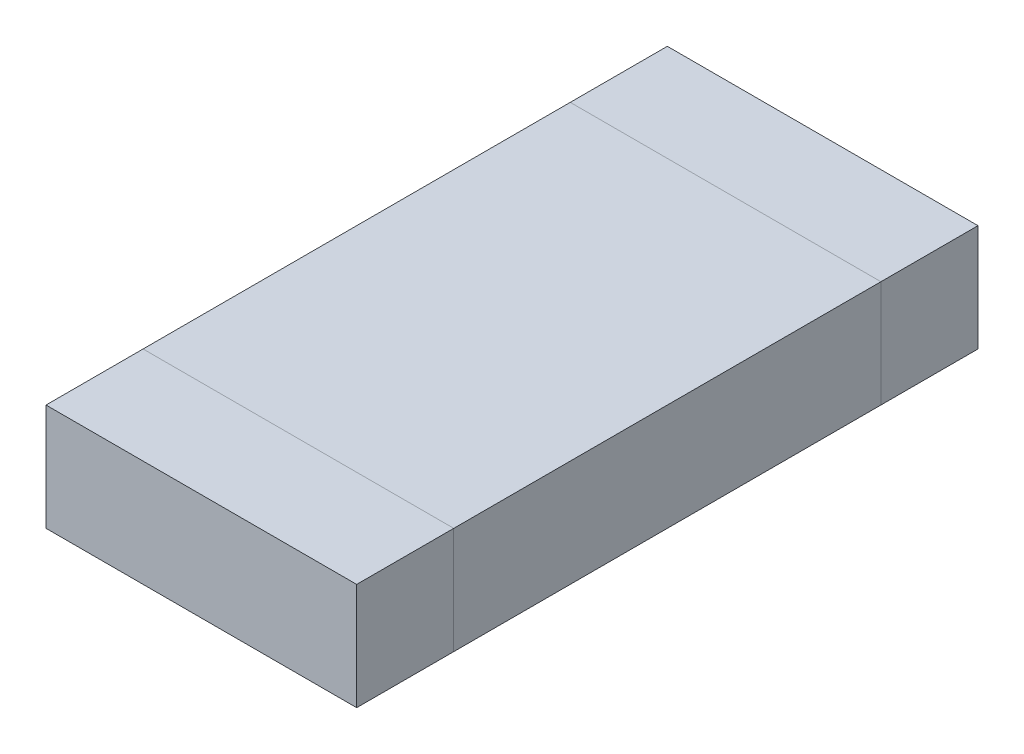
SolidWorks part; units mm, degrees
ref_plane "Front Plane" through (0, 0, 0) normal (0, 0, 1) x (1, 0, 0)
ref_plane "Top Plane" through (0, 0, 0) normal (0, 1, 0) x (1, 0, 0)
ref_plane "Right Plane" through (0, 0, 0) normal (1, 0, 0) x (0, 0, -1)
sketch "MainBodyS" plane through (0, 0, 0) normal (0, 1, 0) x (1, 0, 0)
  line L1 (-0.8, 1.1) -> (0.8, 1.1)
  line L2 (-0.8, 1.1) -> (-0.8, -1.1)
  line L3 (-0.8, -1.1) -> (0.8, -1.1)
  line L4 (0.8, 1.1) -> (0.8, -1.1)
  line L5 (-0.8, 1.1) -> (0.8, -1.1) construction
  line L6 (-0.8, -1.1) -> (0.8, 1.1) construction
  point P0 (0, 0)
  dimension "Length" = 2.2
  dimension "Width" = 1.6
extrude "MainBody" add sketch "MainBodyS" along normal blind 0.55
sketch "LeftBodyS" plane through (0, 0, 0) normal (0, -1, 0) x (-1, 0, 0)
  line L1 (0.8, -1.1) -> (-0.8, -1.1)
  line L2 (0.8, -1.1) -> (0.8, -1.6)
  line L3 (0.8, -1.6) -> (-0.8, -1.6)
  line L4 (-0.8, -1.1) -> (-0.8, -1.6)
  dimension "SolderLength" = 0.5
extrude "LeftBody" add sketch "LeftBodyS" against normal up to surface (0.55 mm away) separate body up to face at (0, 0.55, 0)
sketch "RightBodyS" plane through (0, 0, 0) normal (0, -1, 0) x (1, 0, 0)
  line L0 (0.8, 1.1) -> (0.8, 1.6) construction
  line L1 (-0.8, -1.1) -> (0.8, -1.1)
  line L2 (-0.8, -1.1) -> (-0.8, -1.6)
  line L3 (-0.8, -1.6) -> (0.8, -1.6)
  line L4 (0.8, -1.1) -> (0.8, -1.6)
extrude "RightBody" add sketch "RightBodyS" against normal up to surface (0.55 mm away) separate body up to face at (0, 0.55, 0)
